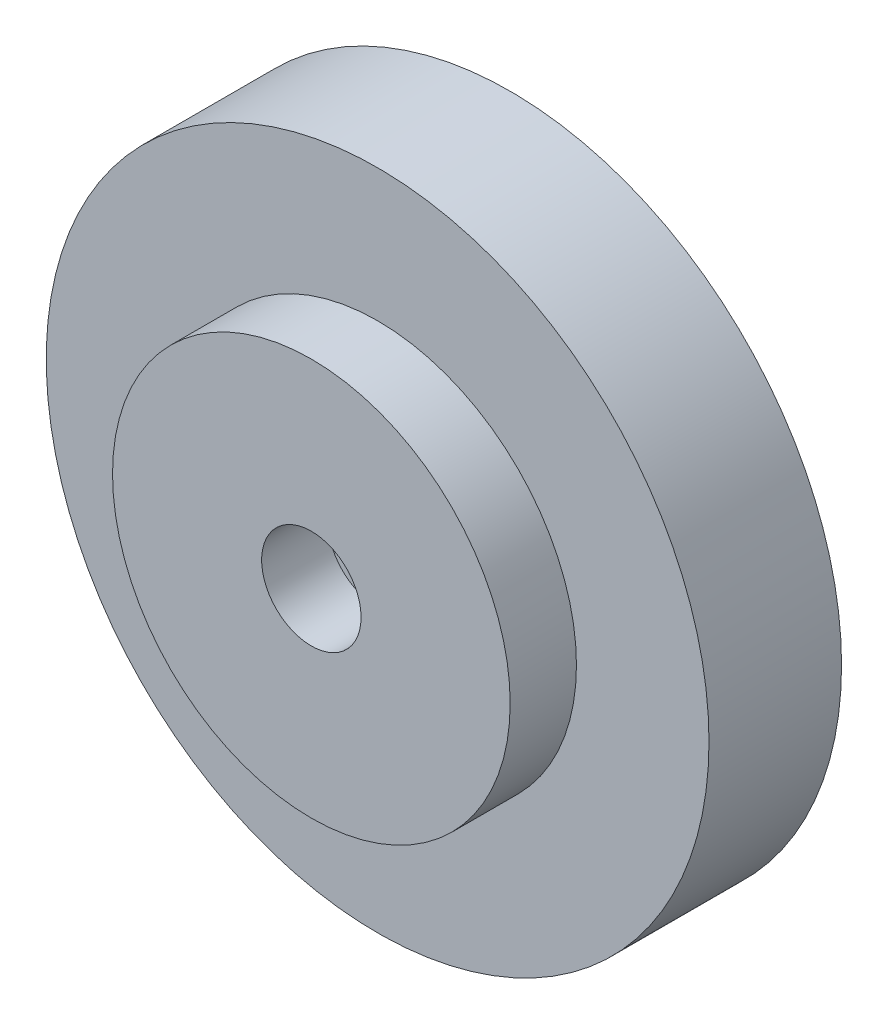
SolidWorks part; units mm, degrees
ref_plane "Front Plane" through (0, 0, 0) normal (0, 0, 1) x (1, 0, 0)
ref_plane "Top Plane" through (0, 0, 0) normal (0, 1, 0) x (1, 0, 0)
ref_plane "Right Plane" through (0, 0, 0) normal (1, 0, 0) x (0, 0, -1)
sketch "Sketch1" plane through (0, 0, 0) normal (0, 0, 1) x (1, 0, 0)
  circle A0 centre (0, 0) radius 50
  dimension "D1" = 100
extrude "Boss-Extrude1" add sketch "Sketch1" along normal blind 20
sketch "Sketch2" plane through (0, 0, 20) normal (0, 0, 1) x (1, 0, 0)
  circle A0 centre (0, 0) radius 30
  dimension "D1" = 60
extrude "Boss-Extrude2" add sketch "Sketch2" along normal blind 10
sketch "Sketch3" plane through (0, 0, 30) normal (0, 0, 1) x (1, 0, 0)
  circle A0 centre (0, 0) radius 7.5
  dimension "D1" = 15
extrude "Cut-Extrude1" cut sketch "Sketch3" against normal blind 10
